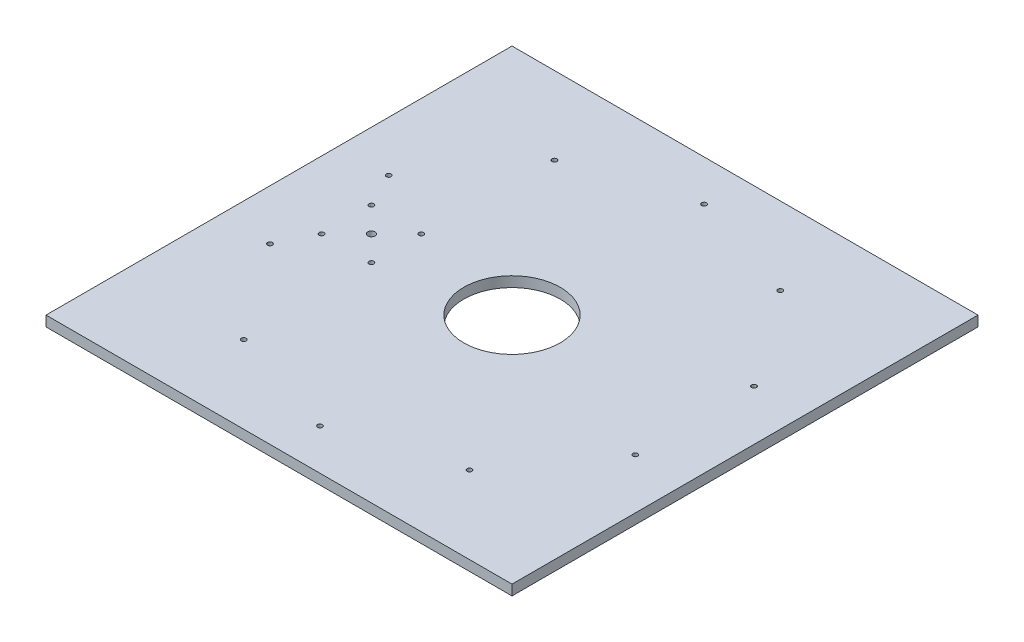
SolidWorks part; units mm, degrees
ref_plane "Front Plane" through (0, 0, 0) normal (0, 0, 1) x (1, 0, 0)
ref_plane "Top Plane" through (0, 0, 0) normal (0, 1, 0) x (1, 0, 0)
ref_plane "Right Plane" through (0, 0, 0) normal (1, 0, 0) x (0, 0, -1)
sketch "Sketch1" plane through (0, 0, 0) normal (0, 1, 0) x (1, 0, 0)
  line L1 (145, -145) -> (-145, -145)
  line L2 (145, -145) -> (145, 145)
  line L3 (145, 145) -> (-145, 145)
  line L4 (-145, -145) -> (-145, 145)
  line L5 (145, -145) -> (-145, 145) construction
  line L6 (145, 145) -> (-145, -145) construction
  point P0 (0, 0)
  dimension "D1" = 290
extrude "Boss-Extrude1" add sketch "Sketch1" along normal blind 6.4
sketch "Sketch2" plane through (0, 6.4, 0) normal (0, 1, 0) x (1, 0, 0)
  line L0 (0, 125) -> (0, 119.525) construction
  line L1 (0, 0) -> (-87.5, 0) construction
  line L3 (-103, -15.5) -> (-72, -15.5) construction
  line L4 (-103, -15.5) -> (-103, 15.5) construction
  line L5 (-103, 15.5) -> (-72, 15.5) construction
  line L6 (-72, -15.5) -> (-72, 15.5) construction
  line L7 (-103, -15.5) -> (-72, 15.5) construction
  line L8 (-103, 15.5) -> (-72, -15.5) construction
  circle A0 centre (0, 0) radius 30
  circle A1 centre (0, 0) radius 125 construction
  circle A2 centre (0, 119.525) radius 1.5
  circle A3 centre (70.255, 96.6978) radius 1.5
  circle A4 centre (113.675, 36.9353) radius 1.5
  circle A5 centre (113.675, -36.9353) radius 1.5
  circle A6 centre (70.255, -96.6978) radius 1.5
  circle A7 centre (0, -119.525) radius 1.5
  circle A8 centre (-70.255, -96.6978) radius 1.5
  circle A9 centre (-113.675, -36.9353) radius 1.5
  circle A10 centre (-113.675, 36.9353) radius 1.5
  circle A11 centre (-70.255, 96.6978) radius 1.5
  circle A12 centre (-87.5, 0) radius 2.25
  circle A13 centre (-103, 15.5) radius 1.5
  circle A14 centre (-72, 15.5) radius 1.5
  circle A15 centre (-72, -15.5) radius 1.5
  circle A16 centre (-103, -15.5) radius 1.5
  point P28 (0, 0)
  dimension "D1" = 60
  dimension "D2" = 250
  dimension "D4" = 3
  dimension "D7" = 4.5
  dimension "D3" = 5.475
  dimension "D6" = 87.5
  dimension "D8" = 31
  dimension "D5" = 10
extrude "Cut-Extrude1" cut sketch "Sketch2" against normal blind 6.4
